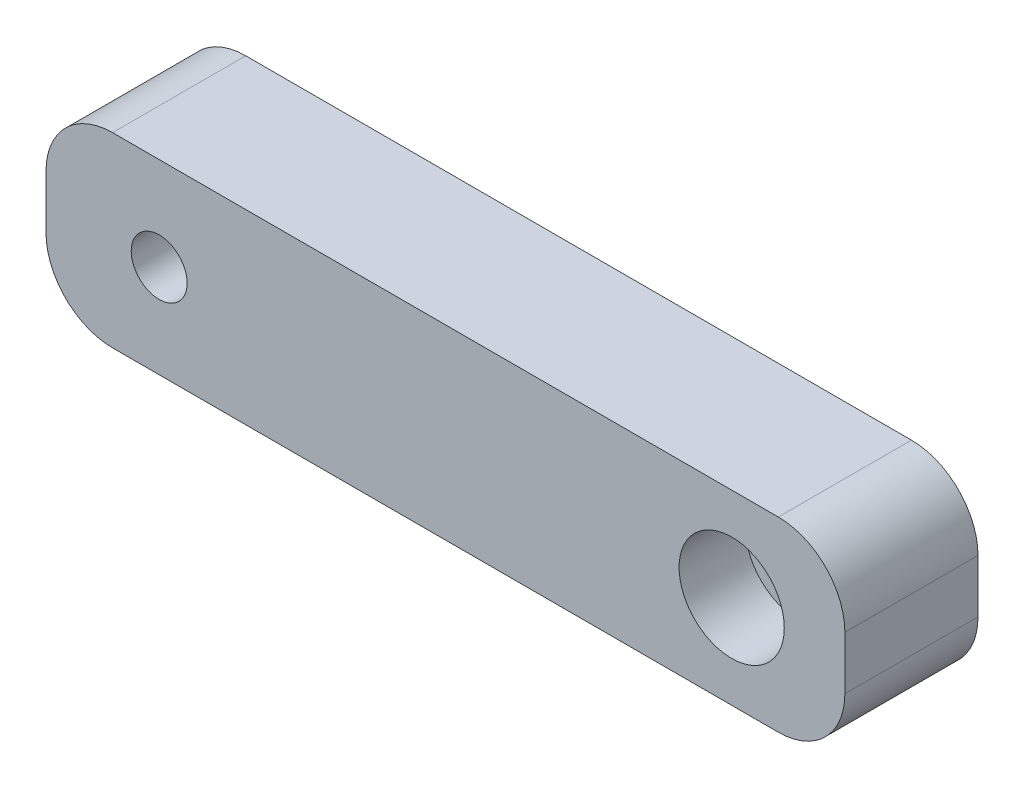
SolidWorks part; units mm, degrees
ref_plane "Front Plane" through (0, 0, 0) normal (0, 0, 1) x (1, 0, 0)
ref_plane "Top Plane" through (0, 0, 0) normal (0, 1, 0) x (1, 0, 0)
ref_plane "Right Plane" through (0, 0, 0) normal (1, 0, 0) x (0, 0, -1)
sketch "Sketch1" plane through (0, 0, 0) normal (0, 0, 1) x (1, 0, 0)
  line L1 (-59.3506, 20.3019) -> (0.6494, 20.3019)
  line L2 (-59.3506, 20.3019) -> (-59.3506, 6.3019)
  line L3 (-59.3506, 6.3019) -> (0.6494, 6.3019)
  line L4 (0.6494, 20.3019) -> (0.6494, 6.3019)
extrude "Boss-Extrude1" add sketch "Sketch1" along normal blind 10 contours L1 L4 L3 L2
fillet "Fillet1" radius 5 1 edges at (-59.3506, 20.3019, 5)
fillet "Fillet2" radius 5 3 edges at (0.6494, 6.3019, 5) (0.6494, 20.3019, 5) (-59.3506, 6.3019, 5)
sketch "Sketch2" plane through (0, 0, 0) normal (0, 0, -1) x (-1, 0, 0)
  line L0 (59.3506, 15.3019) -> (59.3506, 11.3019) construction
  line L1 (54.3506, 20.3019) -> (4.3506, 20.3019) construction
  circle A0 centre (50.8506, 13.3019) radius 4
  point P4 (59.3506, 13.3019)
  dimension "D1" = 8.5
  dimension "D2" = 7
extrude "Cut-Extrude2" cut sketch "Sketch2" against normal blind 2.5 contours A0
sketch "Sketch3" plane through (0, 0, 2.5) normal (0, 0, -1) x (-1, 0, 0)
  circle A2 centre (50.8506, 13.3019) radius 2.1
extrude "Cut-Extrude3" cut sketch "Sketch3" against normal blind 2 contours A2
sketch "Sketch4" plane through (0, 0, 10) normal (0, 0, 1) x (1, 0, 0)
  line L0 (0.6494, 15.3019) -> (0.6494, 11.3019) construction
  line L1 (-54.3506, 20.3019) -> (-4.3506, 20.3019) construction
  circle A0 centre (-7.8506, 13.3019) radius 3.95
  dimension "D1" = 8.5
  dimension "D2" = 7
extrude "Cut-Extrude4" cut sketch "Sketch4" against normal blind 5 contours A0
sketch "Sketch5" plane through (0, 0, 5) normal (0, 0, 1) x (1, 0, 0)
  circle A0 centre (-7.8506, 13.3019) radius 2
extrude "Cut-Extrude5" cut sketch "Sketch5" against normal up to next contours A0
sketch "Sketch6" plane through (0, 0, 0) normal (0, 0, -1) x (-1, 0, 0)
  circle A0 centre (7.8506, 13.3019) radius 2
  circle A1 centre (7.8506, 13.3019) radius 4.1
sketch "Sketch7" plane through (0, 0, 4.5) normal (0, 0, -1) x (-1, 0, 0)
  circle A0 centre (50.8506, 13.3019) radius 2.1
extrude "Cut-Extrude6" cut sketch "Sketch7" against normal through all
extrude "Cut-Extrude7" cut sketch "Sketch6" against normal blind 0.5 contours A1
